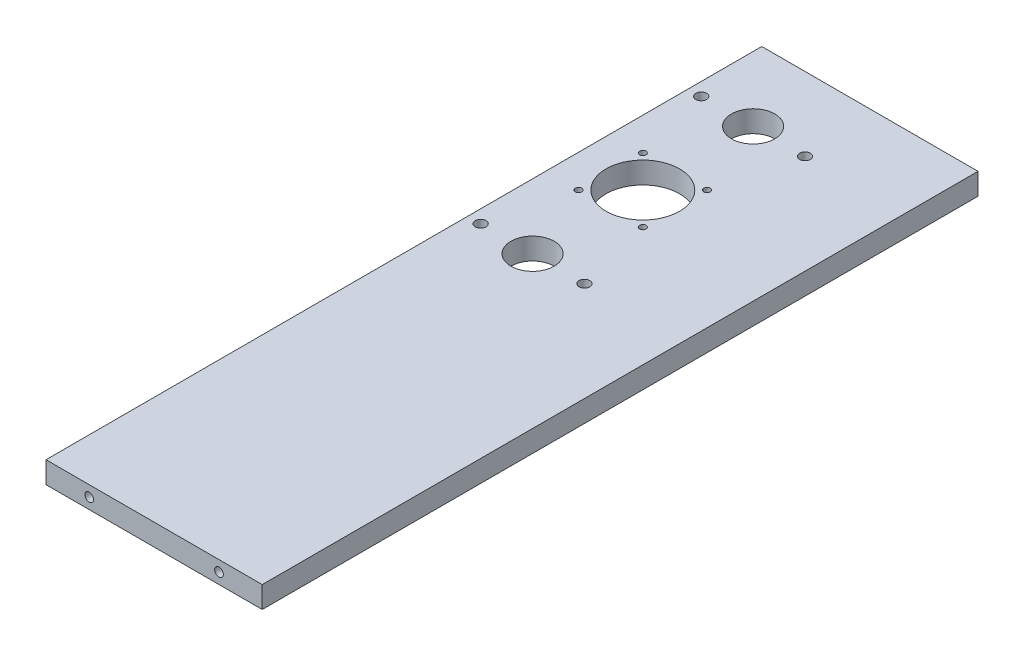
SolidWorks part; units mm, degrees
ref_plane "Front Plane" through (0, 0, 0) normal (0, 0, 1) x (1, 0, 0)
ref_plane "Top Plane" through (0, 0, 0) normal (0, 1, 0) x (1, 0, 0)
ref_plane "Right Plane" through (0, 0, 0) normal (1, 0, 0) x (0, 0, -1)
sketch "Sketch1" plane through (0, 0, 0) normal (0, 1, 0) x (1, 0, 0)
  line L0 (20.7761, 31.1641) -> (20.7761, -299.8359)
  line L1 (20.7761, -299.8359) -> (-79.2239, -299.8359)
  line L2 (-79.2239, -299.8359) -> (-79.2239, 31.1641)
  line L3 (-79.2239, 31.1641) -> (20.7761, 31.1641)
  dimension "D1" = 331
  dimension "D3" = 100
extrude "Boss-Extrude1" add sketch "Sketch1" along normal blind 10
sketch "Sketch2" plane through (0, 10, 0) normal (0, 1, 0) x (1, 0, 0)
  line L2 (-73.2239, -2.8359) -> (-49.2239, -2.8359) construction
  line L3 (-49.2239, -2.8359) -> (-25.2239, -2.8359) construction
  line L4 (-73.2239, -104.8359) -> (-49.2239, -104.8359) construction
  line L5 (-49.2239, -104.8359) -> (-25.2239, -104.8359) construction
  line L6 (-49.2239, -2.8359) -> (-49.2239, -53.8359) construction
  line L7 (-49.2239, -53.8359) -> (-49.2239, -104.8359) construction
  line L9 (-64.0732, -38.9867) -> (-64.0732, -68.6851) construction
  line L10 (-64.0732, -68.6851) -> (-34.3747, -68.6851) construction
  line L11 (-34.3747, -68.6851) -> (-34.3747, -38.9867) construction
  line L12 (-34.3747, -38.9867) -> (-64.0732, -38.9867) construction
  line L13 (-79.2239, 31.1641) -> (-79.2239, -299.8359) construction
  circle A0 centre (-49.2239, -2.8359) radius 10
  circle A1 centre (-73.2239, -2.8359) radius 2.5
  circle A2 centre (-25.2239, -2.8359) radius 2.5
  circle A3 centre (-49.2239, -104.8359) radius 10
  circle A4 centre (-73.2239, -104.8359) radius 2.5
  circle A5 centre (-25.2239, -104.8359) radius 2.5
  circle A6 centre (-49.2239, -53.8359) radius 17
  circle A7 centre (-49.2239, -53.8359) radius 14.8492 construction
  circle A8 centre (-64.0732, -38.9867) radius 1.5
  circle A9 centre (-34.3747, -38.9867) radius 1.5
  circle A10 centre (-34.3747, -68.6851) radius 1.5
  circle A11 centre (-64.0732, -68.6851) radius 1.5
  dimension "D3" = 20
  dimension "D4" = 5
  dimension "D8" = 34
  dimension "D9" = 3
  dimension "D2" = 195
  dimension "D5" = 24
  dimension "D7" = 102
  dimension "D10" = 42
  dimension "D11" = 30
  dimension "D6" = 2
extrude "Cut-Extrude1" cut sketch "Sketch2" against normal through all
sketch "Sketch3" plane through (0, 0, 299.8359) normal (0, 0, 1) x (1, 0, 0)
  line L0 (-79.2239, 0) -> (-79.2239, 10) construction
  line L1 (-59.2239, 5) -> (-79.2239, 5) construction
  line L2 (0.7761, 5) -> (20.7761, 5) construction
  line L3 (20.7761, 10) -> (20.7761, 0) construction
  circle A0 centre (-59.2239, 5) radius 2
  circle A1 centre (0.7761, 5) radius 2
  point P8 (-79.2239, 5)
  dimension "D1" = 4
  dimension "D2" = 60
extrude "Cut-Extrude2" cut sketch "Sketch3" against normal blind 15
